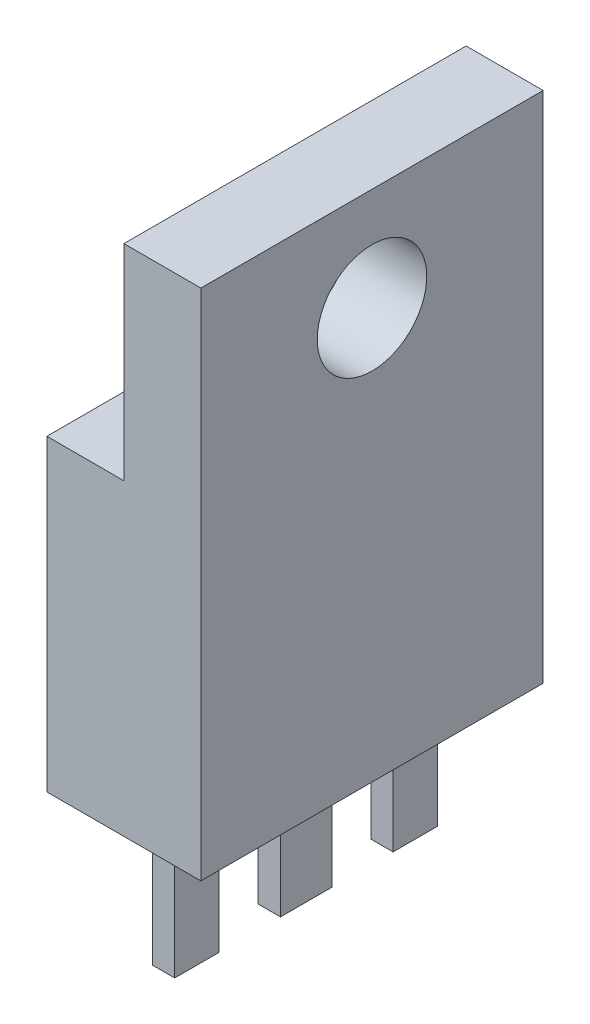
SolidWorks part; units mm, degrees
material "1060-H12"
ref_plane "Спереди" through (0, 0, 0) normal (0, 0, 1) x (1, 0, 0)
ref_plane "Сверху" through (0, 0, 0) normal (0, 1, 0) x (1, 0, 0)
ref_plane "Справа" through (0, 0, 0) normal (1, 0, 0) x (0, 0, -1)
other "Configuration Table"
sketch "Эскиз1" plane through (0, 0, 0) normal (0, 1, 0) x (1, 0, 0)
  line L1 (0, 0) -> (4.5, 0)
  line L2 (0, 0) -> (0, 10)
  line L3 (0, 10) -> (4.5, 10)
  line L4 (4.5, 0) -> (4.5, 10)
  dimension "D1" = 10
  dimension "D2" = 4.5
extrude "Бобышка-Вытянуть1" add sketch "Эскиз1" along normal blind 9
sketch "Эскиз2" plane through (0, 9, 0) normal (0, 1, 0) x (1, 0, 0)
  line L0 (0, 0) -> (4.5, 0) construction
  line L1 (4.5, 10) -> (2.25, 10)
  line L2 (4.5, 10) -> (4.5, 0)
  line L3 (4.5, 0) -> (2.25, 0)
  line L4 (2.25, 10) -> (2.25, 0)
extrude "Бобышка-Вытянуть2" add sketch "Эскиз2" along normal blind 6
sketch "Эскиз3" plane through (2.25, 0, 0) normal (-1, 0, 0) x (0, 0, 1)
  line L0 (-10, 15) -> (0, 15) construction
  line L1 (0, 15) -> (0, 9) construction
  circle A0 centre (-5, 12) radius 1.6
  dimension "D1" = 3.2
  dimension "D2" = 3
  dimension "D3" = 5
extrude "Вырез-Вытянуть1" cut sketch "Эскиз3" against normal through all
sketch "Эскиз4" plane through (0, 0, 0) normal (0, -1, 0) x (1, 0, 0)
  line L0 (0, 0) -> (4.5, 0) construction
  line L1 (1.925, -1.16) -> (2.575, -1.16)
  line L2 (1.925, -1.16) -> (1.925, -2.46)
  line L3 (1.925, -2.46) -> (2.575, -2.46)
  line L4 (2.575, -1.16) -> (2.575, -2.46)
  line L5 (1.925, -4.25) -> (2.575, -4.25)
  line L6 (1.925, -4.25) -> (1.925, -5.75)
  line L7 (1.925, -5.75) -> (2.575, -5.75)
  line L8 (2.575, -4.25) -> (2.575, -5.75)
  line L9 (1.925, -7.54) -> (2.575, -7.54)
  line L10 (1.925, -7.54) -> (1.925, -8.84)
  line L11 (1.925, -8.84) -> (2.575, -8.84)
  line L12 (2.575, -7.54) -> (2.575, -8.84)
  line L13 (4.5, 0) -> (4.5, -10) construction
  point P12 (1.925, -5)
  point P15 (2.575, -5)
  point P18 (2.25, -1.16)
  dimension "D1" = 1.3
  dimension "D2" = 1.5
  dimension "D3" = 5
  dimension "D4" = 2.54
  dimension "D5" = 2.54
  dimension "D6" = 2.25
  dimension "D7" = 0.65
extrude "Бобышка-Вытянуть3" add sketch "Эскиз4" along normal blind 4
